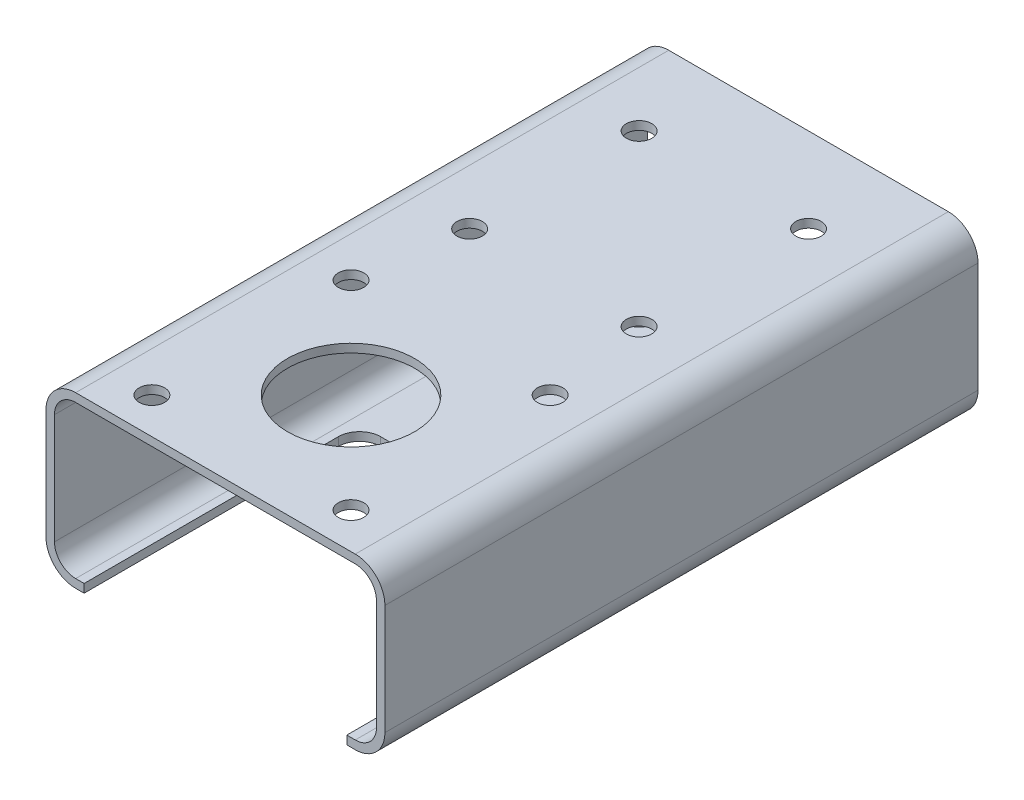
SolidWorks part; units mm, degrees
material "1.0038 (S235JRG2)"
ref_plane "Ebene vorne" through (0, 0, 0) normal (0, 0, 1) x (1, 0, 0)
ref_plane "Ebene oben" through (0, 0, 0) normal (0, 1, 0) x (1, 0, 0)
ref_plane "Ebene rechts" through (0, 0, 0) normal (1, 0, 0) x (0, 0, -1)
sketch "Skizze1" plane through (0, 0, 0) normal (0, 0, 1) x (1, 0, 0)
  line L0 (0, 31) -> (0, 5)
  line L1 (5, 0) -> (71, 0)
  line L2 (76, 5) -> (76, 31)
  line L5 (71, 36) -> (5, 36)
  line L6 (78, 5) -> (78, 31)
  line L7 (71, 38) -> (5, 38)
  line L8 (-2, 31) -> (-2, 5)
  line L9 (5, -2) -> (71, -2)
  arc A5 (76, 31) -> (71, 36) centre (71, 31) ccw
  arc A6 (71, 0) -> (76, 5) centre (71, 5) ccw
  arc A7 (0, 5) -> (5, 0) centre (5, 5) ccw
  arc A8 (5, 36) -> (0, 31) centre (5, 31) ccw
  arc A9 (78, 31) -> (71, 38) centre (71, 31) ccw
  arc A10 (5, 38) -> (-2, 31) centre (5, 31) ccw
  arc A11 (-2, 5) -> (5, -2) centre (5, 5) ccw
  arc A12 (71, -2) -> (78, 5) centre (71, 5) ccw
  point P13 (0, 0)
  dimension "D1" = 5
  dimension "D4" = 40
  dimension "D2" = 2
  dimension "D3" = 80
extrude "Aufsatz-Linear austragen1" add sketch "Skizze1" along normal blind 140
sketch "Skizze2" plane through (0, 38, 0) normal (0, 1, 0) x (-1, 0, 0)
  line L0 (-38, 0) -> (-38, 106.7859) construction
  line L7 (-71, 0) -> (-5, 0) construction
  line L8 (-71, 140) -> (-5, 140) construction
  circle A0 centre (-38, 108) radius 15
  dimension "D2" = 30
  dimension "D1" = 32
extrude "Schnitt-Linear austragen1" cut sketch "Skizze2" against normal blind 10
ref_plane "Ebene1" through (38, 0, 0) normal (1, 0, 0) x (0, 0, -1)
sketch "Skizze3" plane through (0, -2, 0) normal (0, -1, 0) x (1, 0, 0)
  line L0 (38, 0) -> (38, 153.4924) construction
  line L1 (5, 0) -> (71, 0) construction
  line L2 (38, -16.5) -> (38, 16.5) construction
  line L3 (5, 140) -> (71, 140) construction
  line L4 (7, 140) -> (69, 140)
  line L5 (7, 140) -> (7, 80)
  line L6 (12, 75) -> (64, 75)
  line L7 (69, 140) -> (69, 80)
  arc A0 (7, 80) -> (12, 75) centre (12, 80) ccw
  arc A1 (64, 75) -> (69, 80) centre (64, 80) ccw
  point P16 (69, 75)
  dimension "D3" = 5
  dimension "D1" = 62
  dimension "D2" = 65
extrude "Schnitt-Linear austragen2" cut sketch "Skizze3" against normal blind 10
sketch "Skizze4" plane through (0, 38, 0) normal (0, 1, 0) x (1, 0, 0)
  line L0 (38, -108) -> (38, -71.9376) construction
  line L1 (38, -108) -> (92.3986, -108) construction
  circle A0 centre (61.5, -84.5) radius 3
  circle A1 centre (14.5, -84.5) radius 3
  circle A2 centre (14.5, -131.5) radius 3
  circle A3 centre (61.5, -131.5) radius 3
  dimension "D1" = 6
  dimension "D2" = 47
  dimension "D3" = 47
extrude "Schnitt-Linear austragen3" cut sketch "Skizze4" against normal blind 10
sketch "Skizze5" plane through (0, 38, 0) normal (0, 1, 0) x (1, 0, 0)
  line L0 (38, 0) -> (38, -70.5897) construction
  line L1 (71, 0) -> (5, 0) construction
  line L2 (38, -40) -> (87.6811, -40) construction
  circle A0 centre (58, -20) radius 3
  circle A1 centre (18, -20) radius 3
  circle A2 centre (58, -60) radius 3
  circle A3 centre (18, -60) radius 3
  dimension "D1" = 40
  dimension "D2" = 40
  dimension "D4" = 6
  dimension "D3" = 40
extrude "Schnitt-Linear austragen4" cut sketch "Skizze5" against normal blind 60
